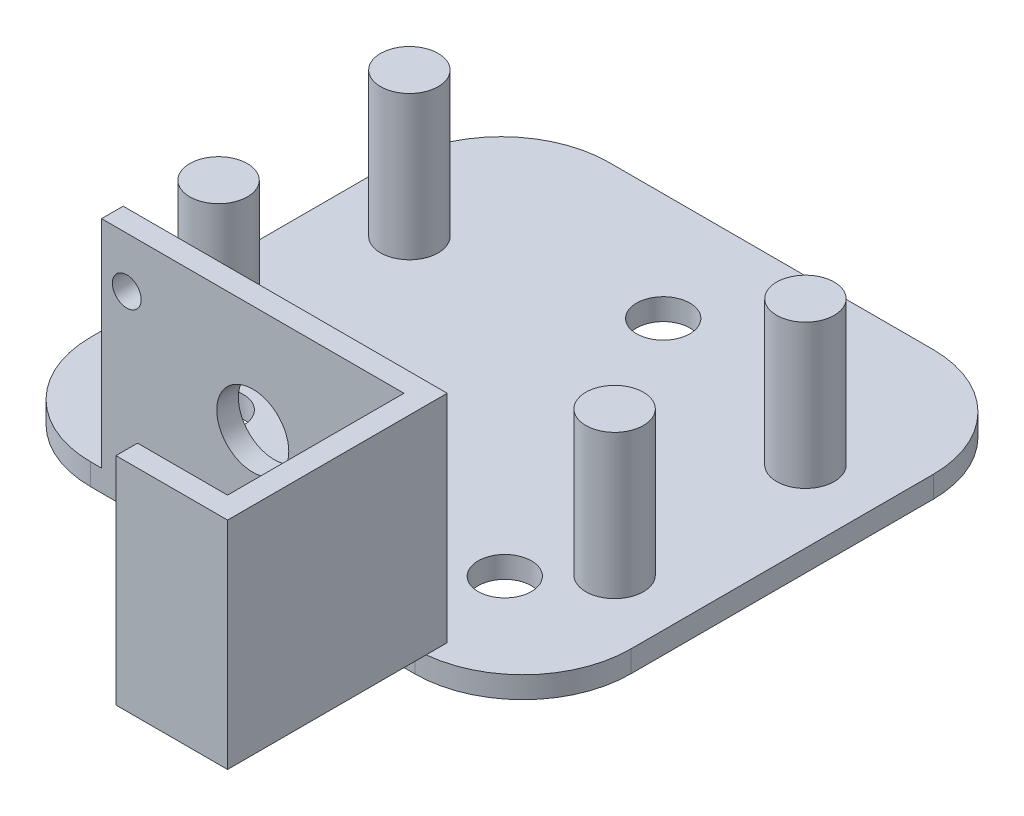
SolidWorks part; units mm, degrees
ref_plane "Front Plane" through (0, 0, 0) normal (0, 0, 1) x (1, 0, 0)
ref_plane "Top Plane" through (0, 0, 0) normal (0, 1, 0) x (1, 0, 0)
ref_plane "Right Plane" through (0, 0, 0) normal (1, 0, 0) x (0, 0, -1)
sketch "Sketch1" plane through (0, 0, 0) normal (0, 1, 0) x (1, 0, 0)
  line L0 (-37.5, 0) -> (37.5, 0) construction
  line L1 (-20, -21) -> (20, -21) construction
  line L2 (0, -21) -> (0, 21) construction
  line L10 (-37.5, -21) -> (-37.5, 21)
  line L11 (37.5, 21) -> (37.5, -21)
  line L12 (22.5, -36) -> (-22.5, -36)
  line L16 (-22.5, 36) -> (22.5, 36)
  arc A0 (-37.5, -21) -> (-22.5, -36) centre (-22.5, -21) ccw
  arc A1 (37.5, -21) -> (22.5, -36) centre (22.5, -21) cw
  circle A5 centre (0, 21) radius 3.7
  arc A9 (-37.5, 21) -> (-22.5, 36) centre (-22.5, 21) cw
  arc A10 (37.5, 21) -> (22.5, 36) centre (22.5, 21) ccw
  circle A11 centre (-20, -21) radius 3.7
  circle A12 centre (20, -21) radius 3.7
  point P0 (-22.5, -21)
  point P4 (0, 0)
  point P6 (0, 21)
  point P7 (22.5, -21)
  point P12 (0, 0)
  point P13 (0, 0)
  point P15 (0, 0)
  point P21 (0, -21)
  point P34 (0, 21)
  dimension "D4" = 7.4
  dimension "D3" = 45
  dimension "D2" = 15
  dimension "D1" = 42
  dimension "D5" = 40
extrude "Boss-Extrude1" add sketch "Sketch1" along normal blind 3
sketch "Sketch3" plane through (0, 3, -40.8767) normal (0, 1, 0) x (-1, 0, 0)
  line L0 (-37.5, 40.8767) -> (37.5, 40.8767) construction
  line L1 (-37.5, 19.8767) -> (-37.5, 61.8767) construction
  line L2 (37.5, 61.8767) -> (37.5, 19.8767) construction
  line L3 (0, 76.8767) -> (0, 4.8767) construction
  line L4 (-22.5, 76.8767) -> (22.5, 76.8767) construction
  line L5 (-27.5, 27.6267) -> (27.5, 27.6267) construction
  line L6 (22.5, 4.8767) -> (-22.5, 4.8767) construction
  line L8 (-27.5, 54.1267) -> (27.5, 54.1267) construction
  line L9 (-27.5, 67.8767) -> (-27.5, 27.6267) construction
  circle A0 centre (-27.5, 27.6267) radius 4
  circle A1 centre (27.5, 27.6267) radius 4
  circle A2 centre (27.5, 54.1267) radius 4
  circle A3 centre (-27.5, 54.1267) radius 4
  point P23 (0, 0)
  dimension "D1" = 8
  dimension "D2" = 27.5
  dimension "D6" = 8
  dimension "D4" = 13.25
extrude "Boss-Extrude3" add sketch "Sketch3" along normal blind 20 contours A0 | A2 | A3 | A1
sketch "Sketch5" plane through (0, 3, 0) normal (0, 1, 0) x (1, 0, 0)
  line L0 (22.5, -36) -> (-22.5, -36) construction
  line L1 (22.5, -36) -> (-22.5, -36) construction
  line L2 (24, -36) -> (24, -33)
  line L3 (24, -33) -> (-21, -33)
  line L4 (-21, -33) -> (-21, -36)
  line L5 (24, -63.5) -> (24, -36)
  line L6 (24, -63.5) -> (21, -63.5)
  line L7 (21, -63.5) -> (21, -36)
  line L9 (-21, -36) -> (21, -36)
  point P0 (0, -36)
  point P10 (30, -36)
  point P13 (0, -36)
  dimension "D1" = 45
  dimension "D2" = 3
  dimension "D3" = 3
  dimension "D4" = 27.5
extrude "Boss-Extrude5" add sketch "Sketch5" along normal blind 30
sketch "Sketch6" plane through (0, 0, 36) normal (0, 0, 1) x (1, 0, 0)
  line L0 (-22.5, 3) -> (21, 3) construction
  line L1 (0, 33) -> (0, 3) construction
  line L2 (-21, 33) -> (21, 33) construction
  line L6 (-17.5, 26) -> (17.5, 26) construction
  circle A0 centre (0, 18) radius 5
  circle A1 centre (-17.5, 26) radius 2
  circle A2 centre (17.5, 26) radius 2
  point P19 (0, 26)
  dimension "D1" = 10
  dimension "D4" = 4
  dimension "D2" = 35
  dimension "D3" = 8
extrude "Cut-Extrude1" cut sketch "Sketch6" against normal up to next
sketch "Sketch8" plane through (21, 0, 0) normal (-1, 0, 0) x (0, 0, 1)
  line L0 (63.5, 3) -> (36, 3) construction
  line L1 (63.5, 33) -> (60.5, 33)
  line L2 (63.5, 33) -> (63.5, 3)
  line L3 (63.5, 3) -> (60.5, 3)
  line L4 (60.5, 33) -> (60.5, 3)
  dimension "D1" = 3
extrude "Boss-Extrude6" add sketch "Sketch8" along normal blind 12.5
